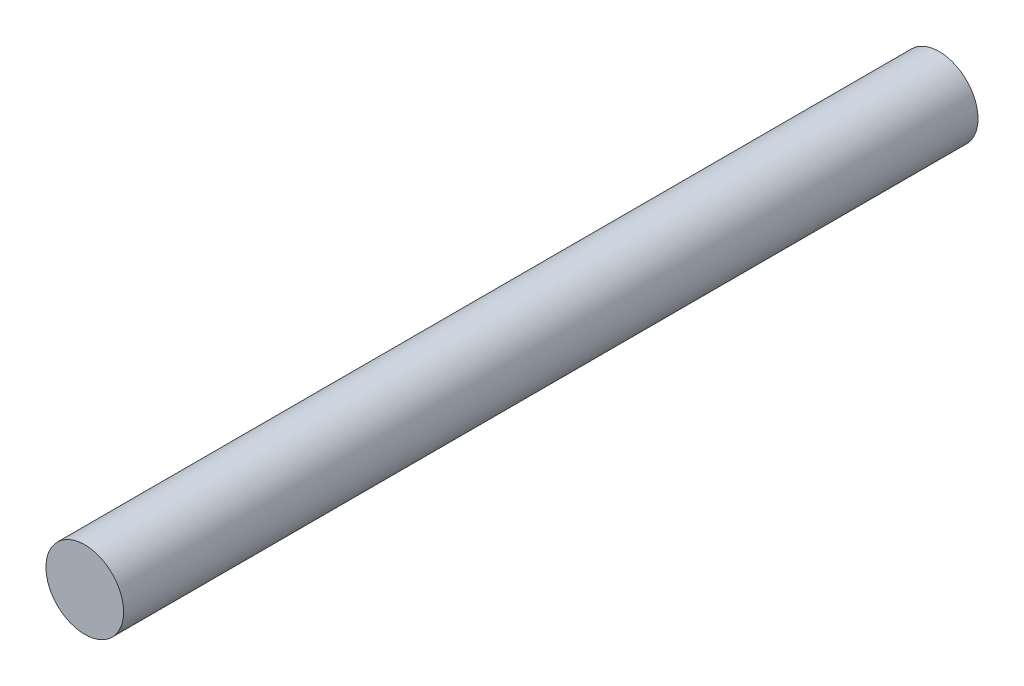
SolidWorks part; units mm, degrees
ref_plane "前视基准面" through (0, 0, 0) normal (0, 0, 1) x (1, 0, 0)
ref_plane "上视基准面" through (0, 0, 0) normal (0, 1, 0) x (1, 0, 0)
ref_plane "右视基准面" through (0, 0, 0) normal (1, 0, 0) x (0, 0, -1)
sketch "草图1" plane through (0, 0, 0) normal (0, 0, 1) x (1, 0, 0)
  circle A0 centre (0, 0) radius 1
  dimension "D1" = 2
extrude "凸台-拉伸1" add sketch "草图1" along normal blind 22
